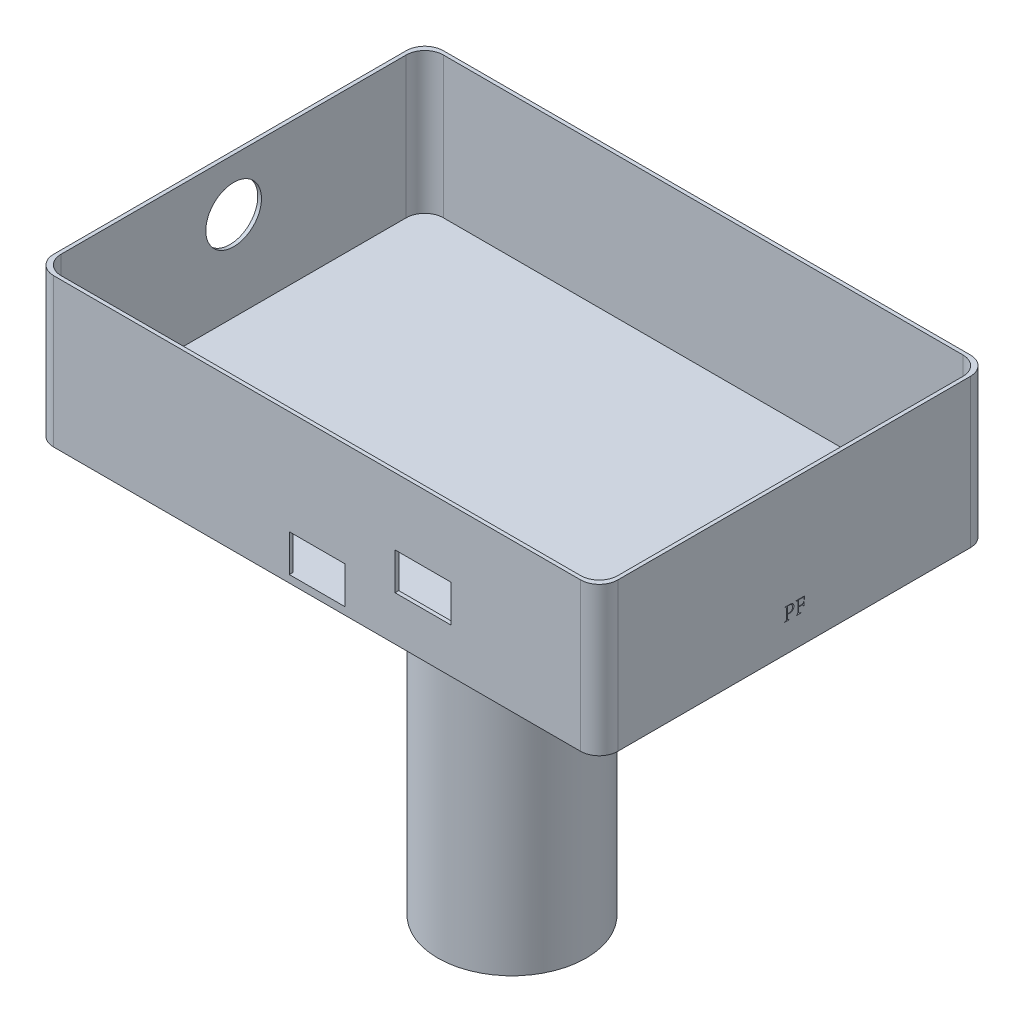
SolidWorks part; units mm, degrees
ref_plane "前视基准面" through (0, 0, 0) normal (0, 0, 1) x (1, 0, 0)
ref_plane "上视基准面" through (0, 0, 0) normal (0, 1, 0) x (1, 0, 0)
ref_plane "右视基准面" through (0, 0, 0) normal (1, 0, 0) x (0, 0, -1)
other "Configuration Table"
sketch "草图1" plane through (0, 0, 0) normal (0, 1, 0) x (1, 0, 0)
  line L1 (71, -52.5) -> (-71, -52.5)
  line L2 (76, -47.5) -> (76, 47.5)
  line L3 (71, 52.5) -> (-71, 52.5)
  line L4 (-76, -47.5) -> (-76, 47.5)
  line L5 (76, -52.5) -> (-76, 52.5) construction
  line L6 (76, 52.5) -> (-76, -52.5) construction
  arc A0 (76, 47.5) -> (71, 52.5) centre (71, 47.5) ccw
  arc A1 (-71, 52.5) -> (-76, 47.5) centre (-71, 47.5) ccw
  arc A2 (71, -52.5) -> (76, -47.5) centre (71, -47.5) ccw
  arc A3 (-71, -52.5) -> (-76, -47.5) centre (-71, -47.5) cw
  point P0 (0, 0)
  dimension "D3" = 5
  dimension "D1" = 152
  dimension "D2" = 105
extrude "凸台-拉伸4" add sketch "草图1" along normal blind 40
sketch "草图4" plane through (0, 0, 0) normal (0, -1, 0) x (1, 0, 0)
  circle A0 centre (0, 0) radius 20
extrude "凸台-拉伸5" add sketch "草图4" along normal blind 100
sketch "草图5" plane through (0, 40, 0) normal (0, 1, 0) x (1, 0, 0)
  line L1 (70, -51.5) -> (-70, -51.5)
  line L2 (75, -46.5) -> (75, 46.5)
  line L3 (70, 51.5) -> (-70, 51.5)
  line L4 (-75, -46.5) -> (-75, 46.5)
  line L5 (75, -51.5) -> (-75, 51.5) construction
  line L6 (75, 51.5) -> (-75, -51.5) construction
  arc A0 (-70, -51.5) -> (-75, -46.5) centre (-70, -46.5) cw
  arc A1 (70, -51.5) -> (75, -46.5) centre (70, -46.5) ccw
  arc A2 (75, 46.5) -> (70, 51.5) centre (70, 46.5) ccw
  arc A3 (-70, 51.5) -> (-75, 46.5) centre (-70, 46.5) ccw
  point P0 (0, 0)
  dimension "D3" = 5
  dimension "D1" = 150
  dimension "D2" = 103
extrude "切除-拉伸1" cut sketch "草图5" against normal blind 38
ref_plane "基准面1" through (-71, 0, 52.5) normal (1, 0, 0) x (0, 0, -1)
sketch "草图9" plane through (0, 0, 52.5) normal (0, 0, 1) x (1, 0, 0)
  line L0 (-71, 0) -> (71, 0) construction
  line L1 (-7.5, 12) -> (7.5, 12)
  line L2 (-7.5, 12) -> (-7.5, 2)
  line L3 (-7.5, 2) -> (7.5, 2)
  line L4 (7.5, 12) -> (7.5, 2)
  line L5 (71, 40) -> (71, 0) construction
  dimension "D1" = 2
  dimension "D2" = 10
  dimension "D3" = 15
  dimension "D4" = 63.5
extrude "切除-拉伸2" cut sketch "草图9" against normal blind 38
sketch "草图13" plane through (-76, 0, 0) normal (-1, 0, 0) x (0, 0, 1)
  line L0 (-47.5, 0) -> (47.5, 0) construction
  circle A0 centre (0, 26) radius 7.5
  dimension "D1" = 26
extrude "切除-拉伸4" cut sketch "草图13" against normal blind 38
sketch "草图14" plane through (0, 0, 52.5) normal (0, 0, 1) x (1, 0, 0)
  line L0 (-71, 0) -> (71, 0) construction
  line L1 (21, 22) -> (36, 22)
  line L2 (21, 22) -> (21, 12)
  line L3 (21, 12) -> (36, 12)
  line L4 (36, 22) -> (36, 12)
  line L5 (76, 40) -> (76, 0) construction
  point P4 (28.5, 12)
  dimension "D1" = 12
  dimension "D2" = 15
  dimension "D3" = 10
  dimension "D4" = 40
extrude "切除-拉伸6" cut sketch "草图14" against normal blind 33
sketch "草图15" plane through (76, 0, 0) normal (1, 0, 0) x (0, 0, -1)
  text T0 "PF\r\n" font "@Adobe 宋体 Std L" height 3.5
extrude "切除-拉伸7" cut sketch "草图15" against normal blind 0.5
